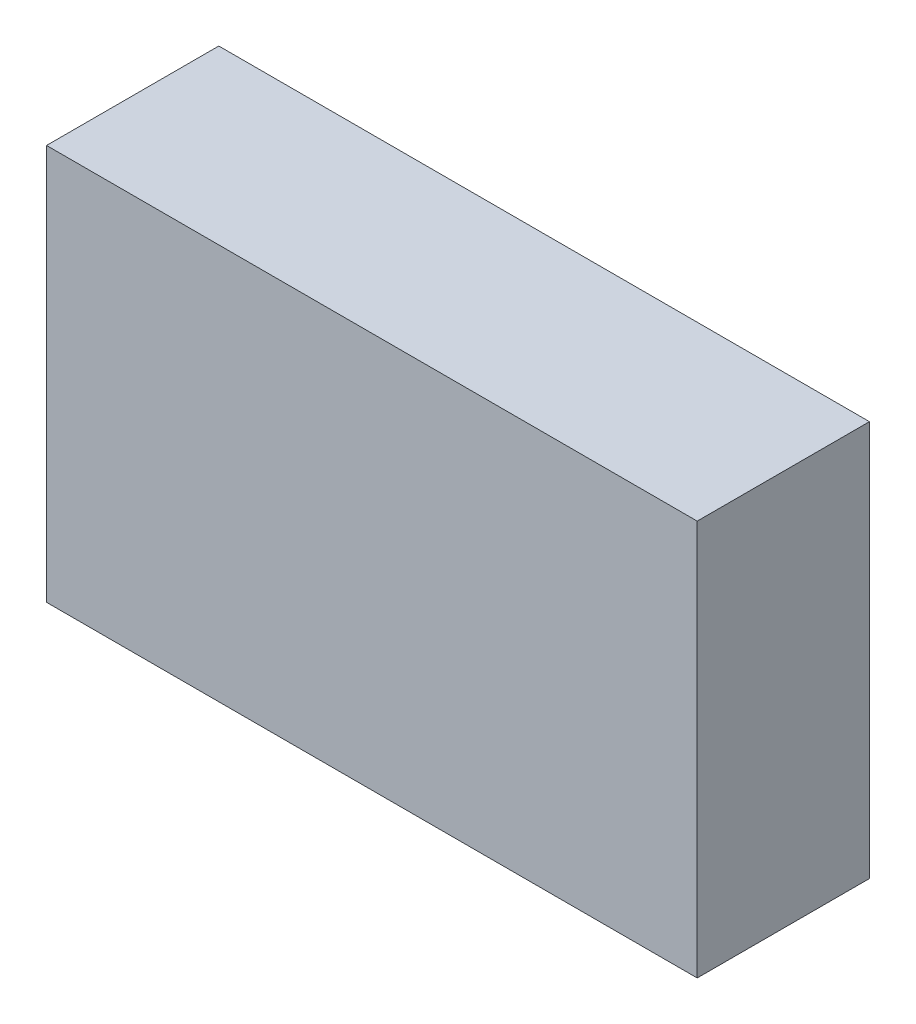
SolidWorks part; units mm, degrees
ref_plane "Front Plane" through (0, 0, 0) normal (0, 0, 1) x (1, 0, 0)
ref_plane "Top Plane" through (0, 0, 0) normal (0, 1, 0) x (1, 0, 0)
ref_plane "Right Plane" through (0, 0, 0) normal (1, 0, 0) x (0, 0, -1)
sketch "CurveSketch" plane through (0, 0, 0) normal (0, 0, 1) x (1, 0, 0)
  line L1 (-21.9595, 2.3135) -> (7.1775, 2.3135)
  line L2 (-21.9595, 2.3135) -> (-21.9595, 20.0325)
  line L3 (-21.9595, 20.0325) -> (7.1775, 20.0325)
  line L4 (7.1775, 2.3135) -> (7.1775, 20.0325)
extrude "CurveBoss" add sketch "CurveSketch" along normal blind 7.713
